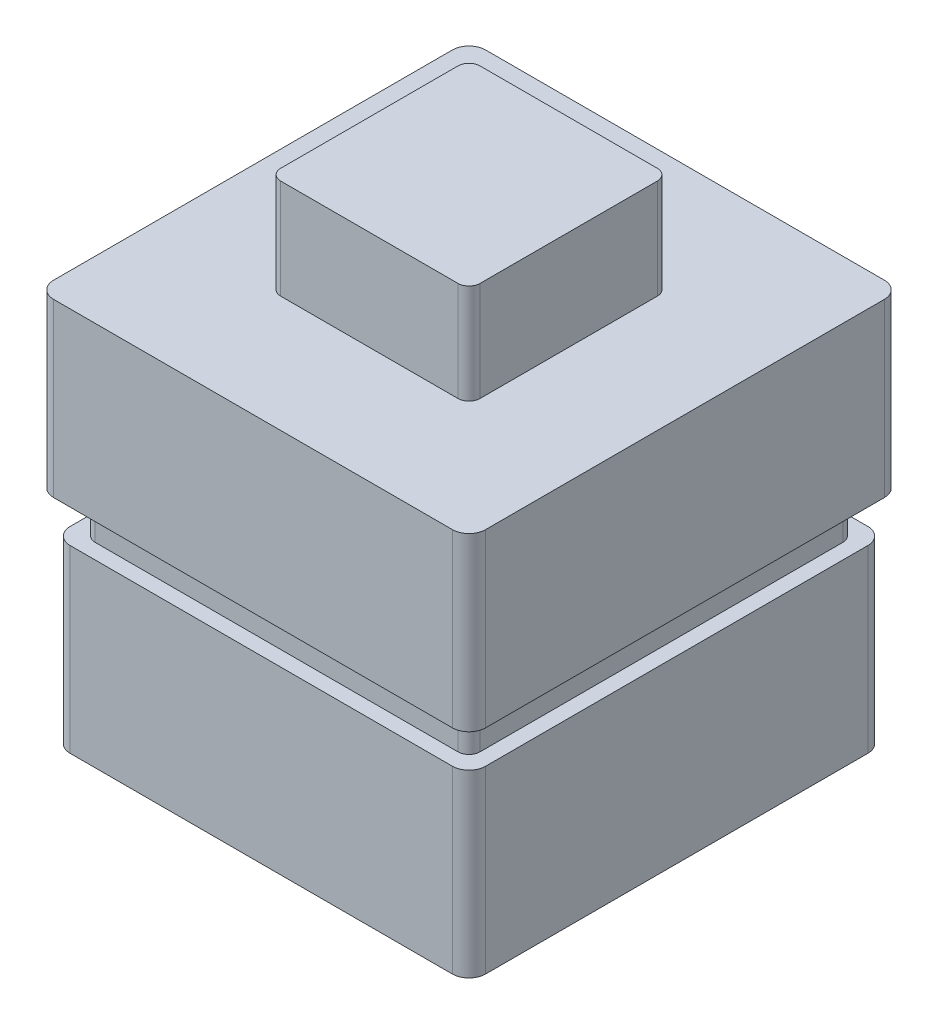
SolidWorks part; units mm, degrees
ref_plane "Front Plane" through (0, 0, 0) normal (0, 0, 1) x (1, 0, 0)
ref_plane "Top Plane" through (0, 0, 0) normal (0, 1, 0) x (1, 0, 0)
ref_plane "Right Plane" through (0, 0, 0) normal (1, 0, 0) x (0, 0, -1)
sketch "Sketch1" plane through (0, 0, 0) normal (0, 1, 0) x (1, 0, 0)
  line L0 (-7.2, 89.3) -> (7.2, 89.3)
  line L1 (7.8, 88.7) -> (7.8, 74.3)
  line L2 (7.2, 73.7) -> (-7.2, 73.7)
  line L3 (-7.8, 74.3) -> (-7.8, 88.7)
  arc A0 (-7.8, 88.7) -> (-7.2, 89.3) centre (-7.2, 88.7) cw
  arc A1 (7.2, 89.3) -> (7.8, 88.7) centre (7.2, 88.7) cw
  arc A2 (7.8, 74.3) -> (7.2, 73.7) centre (7.2, 74.3) cw
  arc A3 (-7.2, 73.7) -> (-7.8, 74.3) centre (-7.2, 74.3) cw
extrude "Upper" add sketch "Sketch1" along normal blind 6.2 from offset 67
sketch "Sketch2" plane through (0, 0, 0) normal (0, 1, 0) x (1, 0, 0)
  line L0 (-6.55, 88.45) -> (6.55, 88.45)
  line L1 (6.95, 88.05) -> (6.95, 74.95)
  line L2 (6.55, 74.55) -> (-6.55, 74.55)
  line L3 (-6.95, 74.95) -> (-6.95, 88.05)
  arc A0 (-6.95, 88.05) -> (-6.55, 88.45) centre (-6.55, 88.05) cw
  arc A1 (6.55, 88.45) -> (6.95, 88.05) centre (6.55, 88.05) cw
  arc A2 (6.95, 74.95) -> (6.55, 74.55) centre (6.55, 74.95) cw
  arc A3 (-6.55, 74.55) -> (-6.95, 74.95) centre (-6.55, 74.95) cw
extrude "Neck" add sketch "Sketch2" along normal blind 1.7 from offset 65.5
sketch "Sketch3" plane through (0, 0, 0) normal (0, 1, 0) x (1, 0, 0)
  line L0 (-6.9, 89) -> (6.9, 89)
  line L1 (7.5, 88.4) -> (7.5, 74.6)
  line L2 (6.9, 74) -> (-6.9, 74)
  line L3 (-7.5, 74.6) -> (-7.5, 88.4)
  arc A0 (-7.5, 88.4) -> (-6.9, 89) centre (-6.9, 88.4) cw
  arc A1 (6.9, 89) -> (7.5, 88.4) centre (6.9, 88.4) cw
  arc A2 (7.5, 74.6) -> (6.9, 74) centre (6.9, 74.6) cw
  arc A3 (-6.9, 74) -> (-7.5, 74.6) centre (-6.9, 74.6) cw
extrude "Body" add sketch "Sketch3" along normal blind 6.5 from offset 59
sketch "Sketch4" plane through (0, 0, 0) normal (0, 1, 0) x (1, 0, 0)
  line L0 (-3.2, 85.1) -> (3.2, 85.1)
  line L1 (3.6, 84.7) -> (3.6, 78.3)
  line L2 (3.2, 77.9) -> (-3.2, 77.9)
  line L3 (-3.6, 78.3) -> (-3.6, 84.7)
  arc A0 (-3.6, 84.7) -> (-3.2, 85.1) centre (-3.2, 84.7) cw
  arc A1 (3.2, 85.1) -> (3.6, 84.7) centre (3.2, 84.7) cw
  arc A2 (3.6, 78.3) -> (3.2, 77.9) centre (3.2, 78.3) cw
  arc A3 (-3.2, 77.9) -> (-3.6, 78.3) centre (-3.2, 78.3) cw
extrude "Stem" add sketch "Sketch4" along normal blind 3.6 from offset 73.2
